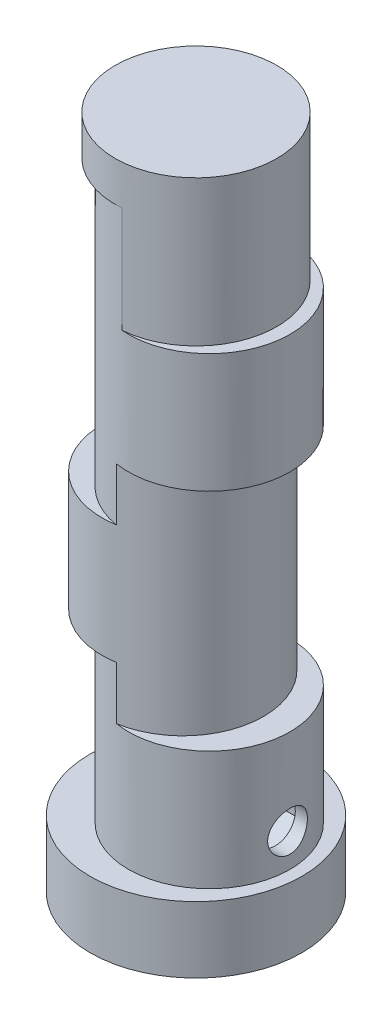
SolidWorks part; units mm, degrees
ref_plane "Front Plane" through (0, 0, 0) normal (0, 0, 1) x (1, 0, 0)
ref_plane "Top Plane" through (0, 0, 0) normal (0, 1, 0) x (1, 0, 0)
ref_plane "Right Plane" through (0, 0, 0) normal (1, 0, 0) x (0, 0, -1)
sketch "Sketch1" plane through (0, 0, 0) normal (0, 1, 0) x (1, 0, 0)
  circle A0 centre (0, 0) radius 8
  dimension "D1" = 16
extrude "Boss-Extrude1" add sketch "Sketch1" along normal blind 5
sketch "Sketch2" plane through (0, 5, 0) normal (0, 1, 0) x (1, 0, 0)
  line L0 (0, 0) -> (1, 0) construction
  circle A0 centre (1, 0) radius 6.1
  dimension "D2" = 12.2
  dimension "D1" = 1
extrude "Boss-Extrude2" add sketch "Sketch2" along normal blind 9
sketch "Sketch3" plane through (0, 14, 0) normal (0, 1, 0) x (1, 0, 0)
  line L0 (0, 0) -> (-1, 0) construction
  circle A0 centre (-1, 0) radius 6.1
  dimension "D2" = 12.2
  dimension "D1" = 1
extrude "Boss-Extrude3" add sketch "Sketch3" along normal blind 17
sketch "Sketch4" plane through (0, 31, 0) normal (0, 1, 0) x (1, 0, 0)
  line L0 (0, 0) -> (1, 0) construction
  circle A0 centre (1, 0) radius 6.1
  dimension "D2" = 12.2
  dimension "D1" = 1
extrude "Boss-Extrude4" add sketch "Sketch4" along normal blind 9
sketch "Sketch5" plane through (0, 31, 0) normal (0, 1, 0) x (1, 0, 0)
  arc A2 (0, 6.0175) -> (0, -6.0175) centre (1, 0) ccw
  arc A3 (0, 6.0175) -> (0, -6.0175) centre (-1, 0) ccw
  arc A4 (0, 6.0175) -> (0, -6.0175) centre (1, 0) ccw
  arc A5 (0, 6.0175) -> (0, -6.0175) centre (-1, 0) ccw
  dimension "D1" = 0
extrude "Cut-Extrude1" cut sketch "Sketch5" against normal blind 4
sketch "Sketch6" plane through (0, 14, 0) normal (0, -1, 0) x (1, 0, 0)
  arc A2 (0, 6.0175) -> (0, -6.0175) centre (-1, 0) ccw
  arc A3 (0, 6.0175) -> (0, -6.0175) centre (1, 0) ccw
  arc A4 (0, 6.0175) -> (0, -6.0175) centre (-1, 0) ccw
  arc A5 (0, 6.0175) -> (0, -6.0175) centre (1, 0) ccw
  dimension "D1" = 0
extrude "Cut-Extrude2" cut sketch "Sketch6" against normal blind 4
sketch "Sketch7" plane through (0, 40, 0) normal (0, 1, 0) x (1, 0, 0)
  circle A0 centre (0, 0) radius 6.1
  dimension "D1" = 12.2
extrude "Boss-Extrude5" add sketch "Sketch7" along normal blind 11
sketch "Sketch8" plane through (0, 40, 0) normal (0, -1, 0) x (1, 0, 0)
  arc A2 (0.5, 6.0795) -> (0.5, -6.0795) centre (0, 0) ccw
  arc A3 (0.5, 6.0795) -> (0.5, -6.0795) centre (1, 0) ccw
  arc A4 (0.5, 6.0795) -> (0.5, -6.0795) centre (0, 0) ccw
  arc A5 (0.5, 6.0795) -> (0.5, -6.0795) centre (1, 0) ccw
  dimension "D1" = 0
extrude "Cut-Extrude3" cut sketch "Sketch8" against normal blind 8
sketch "Sketch9" plane through (0, 0, 0) normal (0, -1, 0) x (1, 0, 0)
  circle A0 centre (0, 0) radius 3.15
  dimension "D1" = 6.3
extrude "Cut-Extrude4" cut sketch "Sketch9" against normal blind 25
sketch "Sketch10" plane through (0, 0, 0) normal (1, 0, 0) x (0, 0, -1)
  circle A0 centre (0, 7.5) radius 1.5
  point P2 (0, 0)
  dimension "D1" = 3
  dimension "D2" = 7.5
extrude "Cut-Extrude5" cut sketch "Sketch10" along normal through all
sketch "Sketch11" plane through (0, 0, 0) normal (1, 0, 0) x (0, 0, -1)
  line L1 (0, 10.7332) -> (-2.8, 9.1166)
  line L2 (-2.8, 9.1166) -> (-2.8, 5.8834)
  line L3 (-2.8, 5.8834) -> (0, 4.2668)
  line L4 (0, 4.2668) -> (2.8, 5.8834)
  line L5 (2.8, 5.8834) -> (2.8, 9.1166)
  line L6 (2.8, 9.1166) -> (0, 10.7332)
  circle A0 centre (0, 7.5) radius 1.5 construction
  circle A1 centre (0, 7.5) radius 1.5
  circle A2 centre (0, 7.5) radius 2.8 construction
  dimension "D1" = 5.6
extrude "Cut-Extrude6" cut sketch "Sketch11" along normal blind 6
